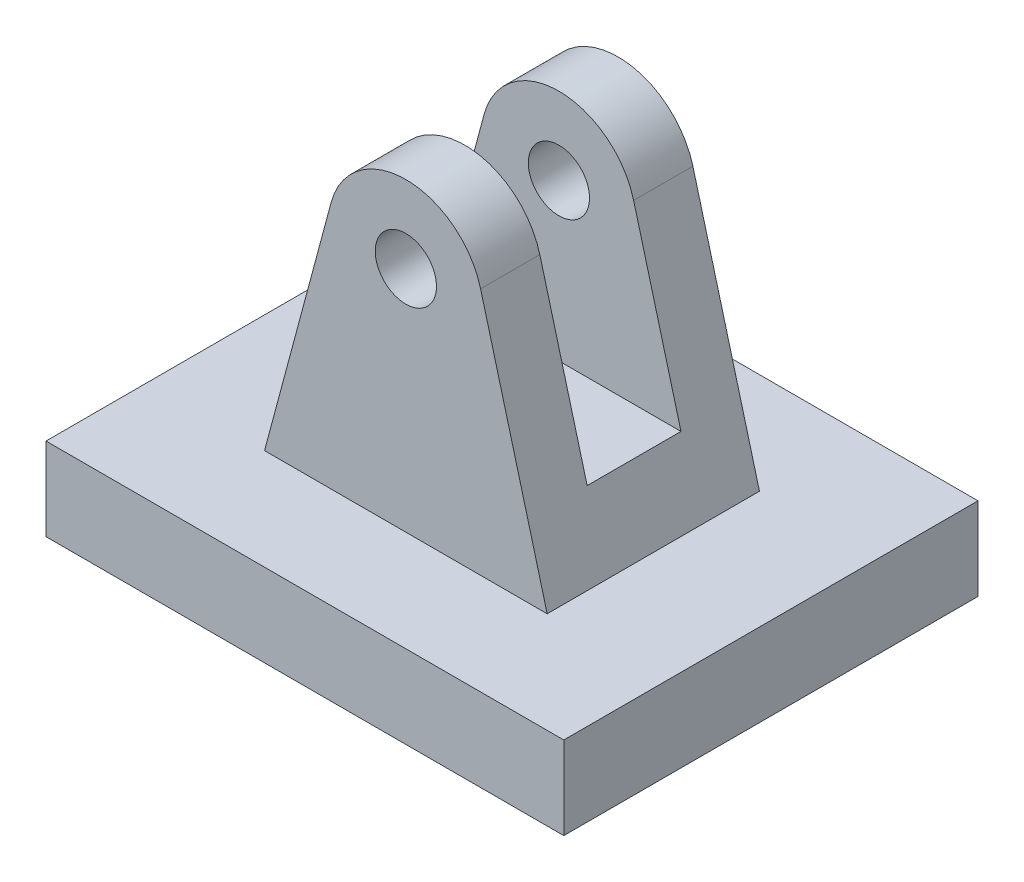
SolidWorks part; units mm, degrees
ref_plane "Front Plane" through (0, 0, 0) normal (0, 0, 1) x (1, 0, 0)
ref_plane "Top Plane" through (0, 0, 0) normal (0, 1, 0) x (1, 0, 0)
ref_plane "Right Plane" through (0, 0, 0) normal (1, 0, 0) x (0, 0, -1)
sketch "Sketch3" plane through (0, 0, 0) normal (0, 1, 0) x (1, 0, 0)
  line L1 (-50, -40) -> (50, -40)
  line L2 (-50, -40) -> (-50, 40)
  line L3 (-50, 40) -> (50, 40)
  line L4 (50, -40) -> (50, 40)
  line L5 (-50, -40) -> (50, 40) construction
  line L6 (-50, 40) -> (50, -40) construction
  point P0 (0, 0)
  dimension "D1" = 80
  dimension "D2" = 100
extrude "Boss-Extrude2" add sketch "Sketch3" along normal blind 16
sketch "Sketch5" plane through (0, 0, 0) normal (0, 0, 1) x (1, 0, 0)
  line L0 (-27.2941, 16) -> (-14.4348, 63.9276)
  line L1 (-50, 16) -> (50, 16) construction
  line L2 (14.4348, 63.9276) -> (27.2941, 16)
  line L6 (-50, 16) -> (50, 16) construction
  line L7 (-27.2941, 16) -> (27.2941, 16)
  arc A0 (-14.4348, 63.9276) -> (14.4348, 63.9276) centre (0, 60.0547) cw
  point P13 (0, 16)
  point P19 (0, 75)
  dimension "D1" = 75
extrude "Boss-Extrude3" add sketch "Sketch5" along normal mid plane 41
sketch "Sketch6" plane through (0, 0, 20.5) normal (0, 0, 1) x (1, 0, 0)
  circle A0 centre (0, 60.0547) radius 5.9118
extrude "Cut-Extrude1" cut sketch "Sketch6" against normal through all
sketch "Sketch8" plane through (0, 0, 0) normal (1, 0, 0) x (0, 0, -1)
  line L0 (20.5, 75) -> (-20.5, 75) construction
  line L1 (-9.0593, 75) -> (9.0593, 75)
  line L2 (-9.0593, 75) -> (-9.0593, 29.8628)
  line L3 (-9.0593, 29.8628) -> (9.0593, 29.8628)
  line L4 (9.0593, 75) -> (9.0593, 29.8628)
  line L5 (0, 16) -> (0, 75) construction
  line L6 (-40, 16) -> (40, 16) construction
  point P6 (0, 29.8628)
  point P12 (0, 0)
extrude "Cut-Extrude2" cut sketch "Sketch8" against normal through all both and the other way through all
